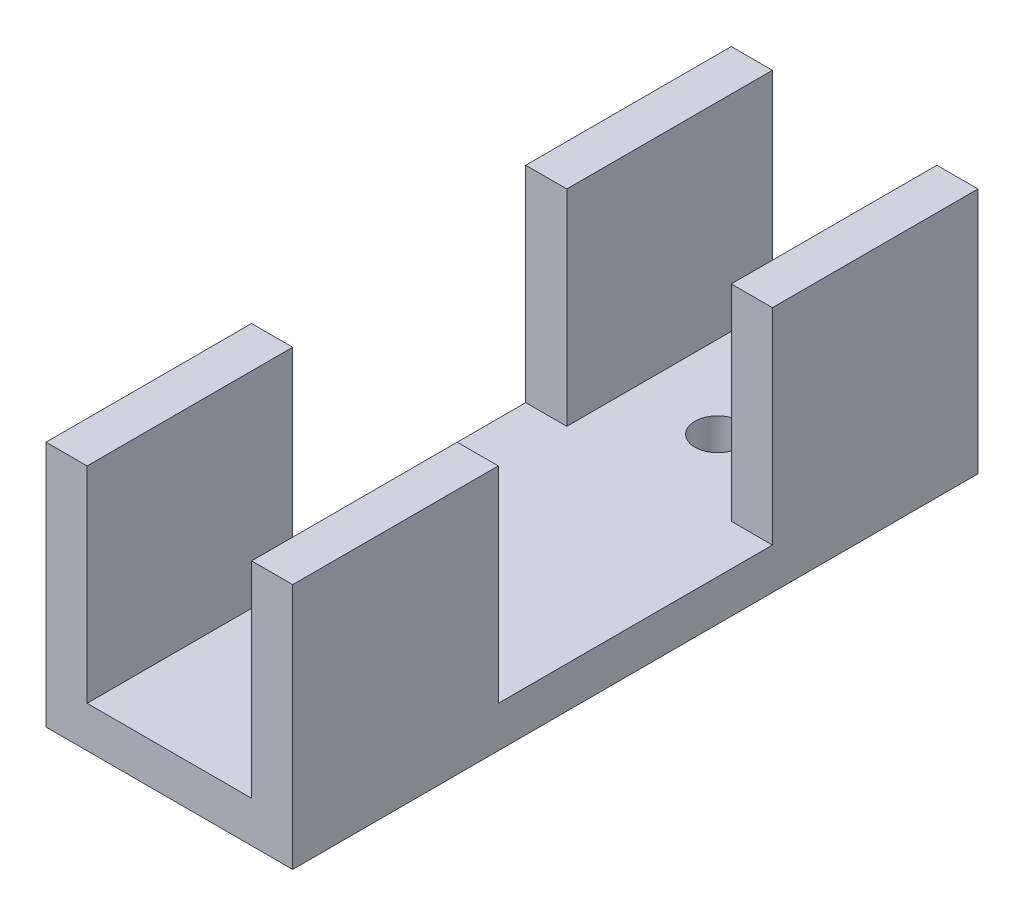
SolidWorks part; units mm, degrees
ref_plane "Front Plane" through (0, 0, 0) normal (0, 0, 1) x (1, 0, 0)
ref_plane "Top Plane" through (0, 0, 0) normal (0, 1, 0) x (1, 0, 0)
ref_plane "Right Plane" through (0, 0, 0) normal (1, 0, 0) x (0, 0, -1)
sketch "Sketch1" plane through (0, 0, 0) normal (0, 1, 0) x (1, 0, 0)
  line L1 (-9, 25) -> (9, 25)
  line L2 (-9, 25) -> (-9, -25)
  line L3 (-9, -25) -> (9, -25)
  line L4 (9, 25) -> (9, -25)
  line L5 (-9, 25) -> (9, -25) construction
  line L6 (-9, -25) -> (9, 25) construction
  point P0 (0, 0)
  dimension "D1" = 18
  dimension "D2" = 50
extrude "Boss-Extrude1" add sketch "Sketch1" along normal blind 3
sketch "Sketch2" plane through (0, 3, 0) normal (0, 1, 0) x (1, 0, 0)
  line L0 (0, 25) -> (0, -25) construction
  line L1 (9, 25) -> (6, 25)
  line L2 (9, 25) -> (9, 10)
  line L3 (9, 10) -> (6, 10)
  line L4 (6, 25) -> (6, 10)
  line L5 (9, 25) -> (-9, 25) construction
  line L6 (-9, -25) -> (9, -25) construction
  line L7 (-9, 0) -> (9, 0) construction
  line L8 (-9, 25) -> (-9, -25) construction
  line L9 (9, -25) -> (9, 25) construction
  line L10 (-6, 25) -> (-6, 10)
  line L11 (-9, 10) -> (-6, 10)
  line L12 (-9, 25) -> (-9, 10)
  line L13 (-9, 25) -> (-6, 25)
  line L14 (-9, -25) -> (-6, -25)
  line L15 (-9, -25) -> (-9, -10)
  line L16 (-9, -10) -> (-6, -10)
  line L17 (-6, -25) -> (-6, -10)
  line L18 (6, -25) -> (6, -10)
  line L19 (9, -10) -> (6, -10)
  line L20 (9, -25) -> (9, -10)
  line L21 (9, -25) -> (6, -25)
  dimension "D1" = 3
  dimension "D2" = 15
extrude "Boss-Extrude2" add sketch "Sketch2" along normal blind 15
sketch "Sketch3" plane through (0, 0, 0) normal (0, -1, 0) x (1, 0, 0)
  line L0 (-9, 0) -> (9, 0) construction
  line L1 (-9, -25) -> (-9, 25) construction
  line L2 (9, 25) -> (9, -25) construction
  circle A0 centre (0, 15) radius 1.65
  circle A1 centre (0, -15) radius 1.65
  dimension "D2" = 3.3
  dimension "D1" = 15
extrude "Cut-Extrude1" cut sketch "Sketch3" against normal up to surface (3 mm away) up to face at (0, 3, 0)
